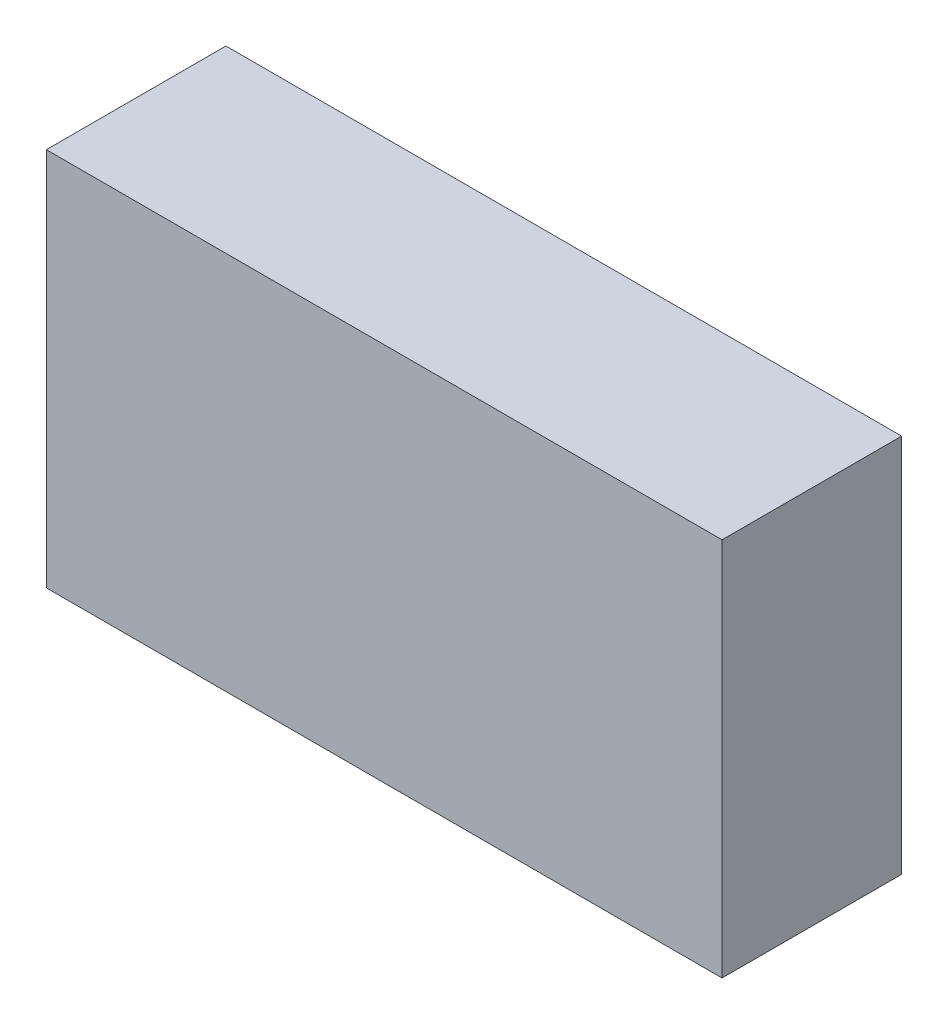
SolidWorks part; units mm, degrees
ref_plane "Front Plane" through (0, 0, 0) normal (0, 0, 1) x (1, 0, 0)
ref_plane "Top Plane" through (0, 0, 0) normal (0, 1, 0) x (1, 0, 0)
ref_plane "Right Plane" through (0, 0, 0) normal (1, 0, 0) x (0, 0, -1)
sketch "Sketch1" plane through (0, 0, 0) normal (0, 0, 1) x (1, 0, 0)
  line L1 (0, 0) -> (36.5, 0)
  line L2 (0, 0) -> (0, 20.5)
  line L3 (0, 20.5) -> (36.5, 20.5)
  line L4 (36.5, 0) -> (36.5, 20.5)
  dimension "D1" = 20.5
  dimension "D2" = 36.5
extrude "Boss-Extrude1" add sketch "Sketch1" along normal blind 9.7
